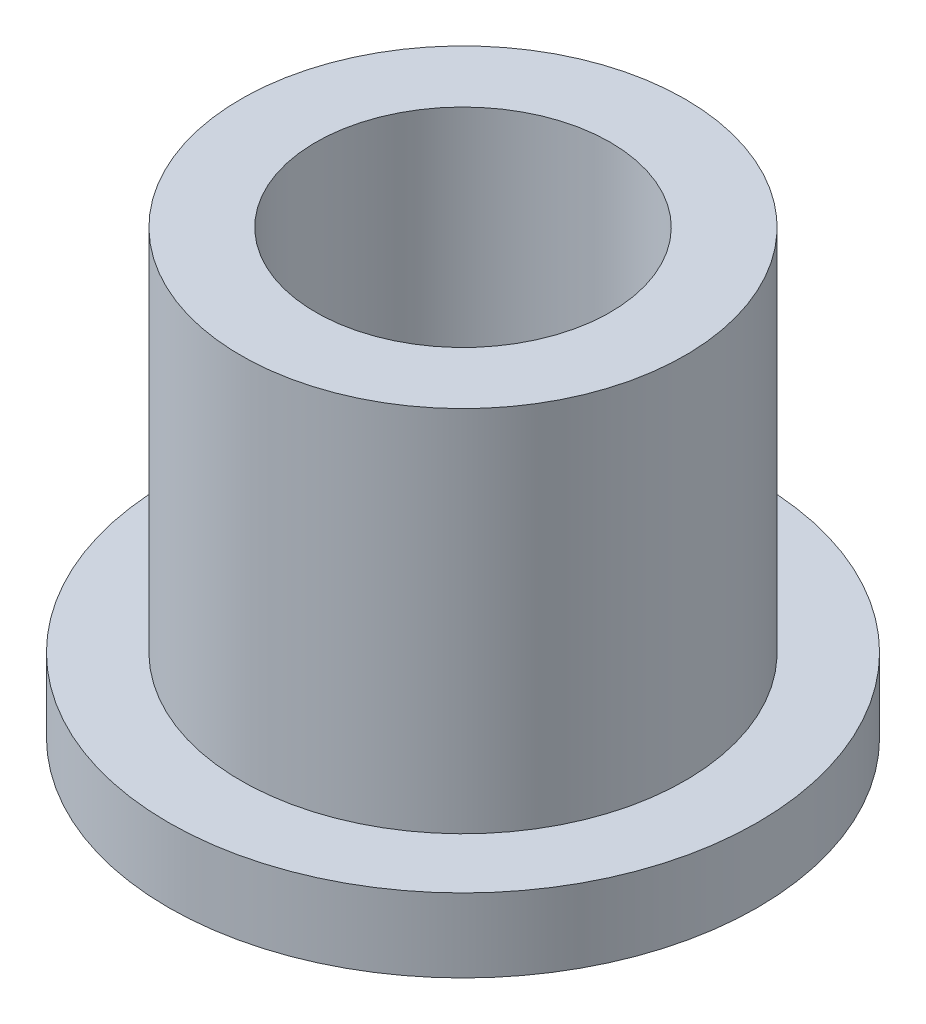
SolidWorks part; units mm, degrees
ref_plane "Front" through (0, 0, 0) normal (0, 0, 1) x (1, 0, 0)
ref_plane "Top" through (0, 0, 0) normal (0, 1, 0) x (1, 0, 0)
ref_plane "Right" through (0, 0, 0) normal (1, 0, 0) x (0, 0, -1)
sketch "Sketch1" plane through (0, 0, 0) normal (0, 1, 0) x (1, 0, 0)
  circle A0 centre (0, 0) radius 3.175
  circle A1 centre (0, 0) radius 4.7879
  circle A2 centre (0, 0) radius 6.35
  dimension "ID" = 6.35
  dimension "OD" = 9.5758
  dimension "FlangeOD" = 12.7
sketch "Sketch2" plane through (0, 0, 0) normal (0, 1, 0) x (1, 0, 0)
  circle A0 centre (0, 0) radius 3.175 construction
  circle A1 centre (0, 0) radius 4.7879 construction
  circle A2 centre (0, 0) radius 3.175
  circle A3 centre (0, 0) radius 4.7879
extrude "Boss-Extrude1" add sketch "Sketch2" along normal blind 9.525
sketch "Sketch3" plane through (0, 0, 0) normal (0, 1, 0) x (1, 0, 0)
  circle A0 centre (0, 0) radius 6.35 construction
  circle A1 centre (0, 0) radius 4.7879 construction
  circle A2 centre (0, 0) radius 6.35
  circle A3 centre (0, 0) radius 4.7879
extrude "Boss-Extrude2" add sketch "Sketch3" along normal blind 1.5875
